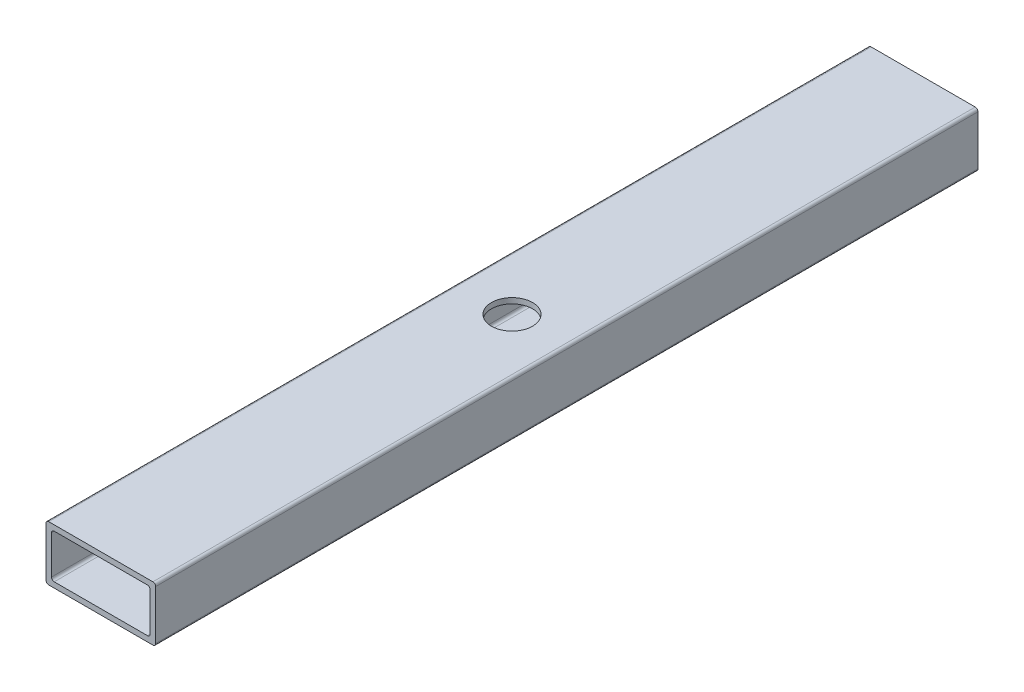
SolidWorks part; units mm, degrees
ref_plane "Plan de face" through (0, 0, 0) normal (0, 0, 1) x (1, 0, 0)
ref_plane "Plan de dessus" through (0, 0, 0) normal (0, 1, 0) x (1, 0, 0)
ref_plane "Plan de droite" through (0, 0, 0) normal (1, 0, 0) x (0, 0, -1)
sketch "Esquisse1" plane through (0, 0, 0) normal (0, 0, 1) x (1, 0, 0)
  line L0 (4, 4) -> (4, 32)
  line L1 (2, -2) -> (78, -2)
  line L2 (0, 0) -> (0, 36)
  line L3 (2, 38) -> (78, 38)
  line L4 (80, 0) -> (80, 36)
  line L5 (6, 34) -> (74, 34)
  line L6 (76, 4) -> (76, 32)
  line L7 (6, 2) -> (74, 2)
  line L8 (4, 2) -> (76, 2) construction
  line L9 (76, 2) -> (76, 34) construction
  line L10 (80, -2) -> (80, 38) construction
  line L11 (0, -2) -> (80, -2) construction
  line L12 (4, 34) -> (76, 34) construction
  line L13 (0, 38) -> (80, 38) construction
  line L14 (0, -2) -> (0, 38) construction
  line L15 (4, 2) -> (4, 34) construction
  arc A0 (74, 2) -> (76, 4) centre (74, 4) ccw
  arc A1 (80, 0) -> (78, -2) centre (78, 0) cw
  arc A2 (74, 34) -> (76, 32) centre (74, 32) cw
  arc A3 (80, 36) -> (78, 38) centre (78, 36) ccw
  arc A4 (0, 36) -> (2, 38) centre (2, 36) cw
  arc A5 (6, 34) -> (4, 32) centre (6, 32) ccw
  arc A6 (6, 2) -> (4, 4) centre (6, 4) cw
  arc A7 (0, 0) -> (2, -2) centre (2, 0) ccw
  dimension "D4" = 2
  dimension "D1" = 40
  dimension "D2" = 80
  dimension "D3" = 4
extrude "Boss.-Extru.1" add sketch "Esquisse1" along normal blind 600
sketch "Esquisse2" plane through (0, 38, 0) normal (0, 1, 0) x (1, 0, 0)
  line L0 (78, -300) -> (2, -300) construction
  line L1 (78, -600) -> (78, 0) construction
  line L2 (2, -600) -> (2, 0) construction
  line L3 (40, -300) -> (40, -80) construction
  circle A0 centre (40, -300) radius 15
  circle A1 centre (40, -80) radius 15 construction
  circle A2 centre (40, -520) radius 15 construction
  dimension "D1" = 30
  dimension "D2" = 30
  dimension "D3" = 220
extrude "Enlèv. mat.-Extru.1" cut sketch "Esquisse2" against normal through all
